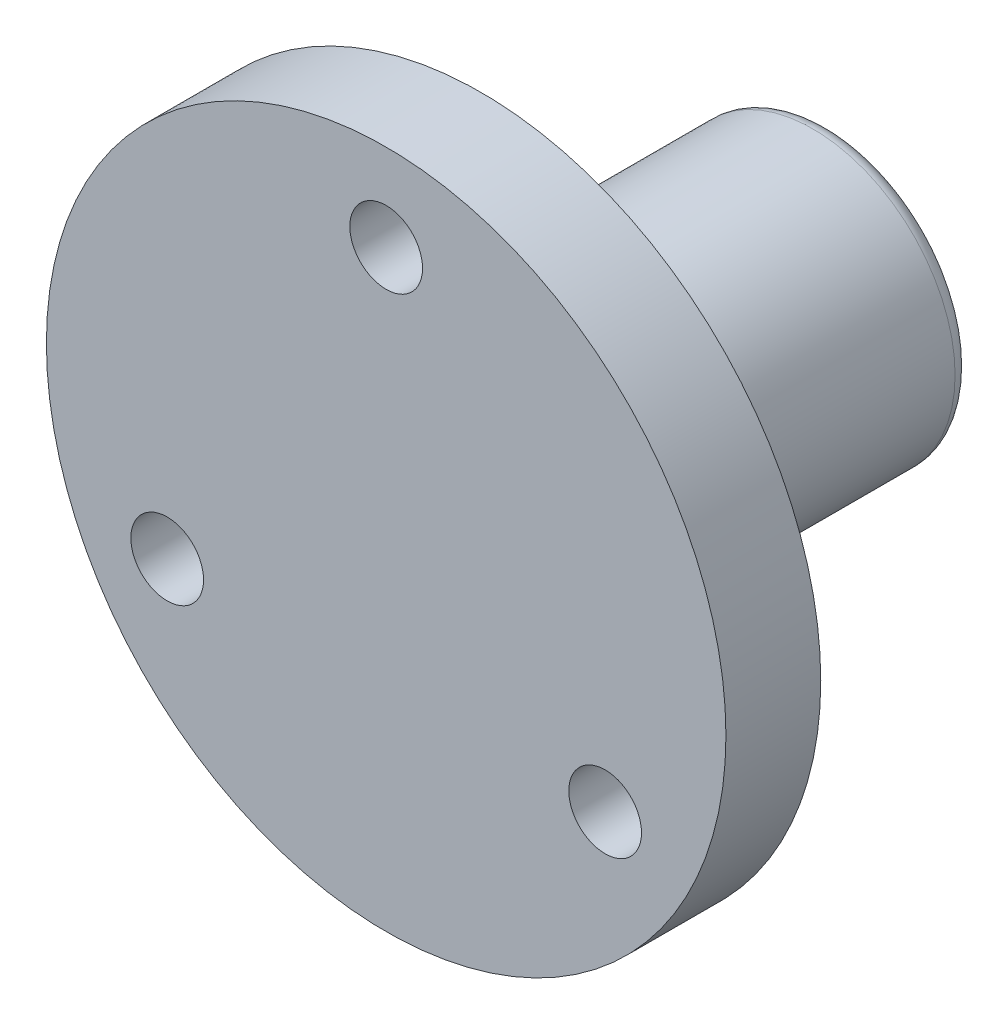
SolidWorks part; units mm, degrees
ref_plane "Front Plane" through (0, 0, 0) normal (0, 0, 1) x (1, 0, 0)
ref_plane "Top Plane" through (0, 0, 0) normal (0, 1, 0) x (1, 0, 0)
ref_plane "Right Plane" through (0, 0, 0) normal (1, 0, 0) x (0, 0, -1)
sketch "Sketch1" plane through (0, 0, 0) normal (0, 0, 1) x (1, 0, 0)
  line L1 (18.147, -4.5837) -> (21.703, -4.5837)
  line L2 (19.925, -4.5837) -> (19.925, -7) construction
  line L3 (18.147, -4.5837) -> (19.925, -7) construction
  arc A0 (18.147, -4.5837) -> (21.703, -4.5837) centre (19.925, -7) ccw
  circle A1 centre (19.925, -7) radius 4.5
  dimension "D1" = 1.5
  dimension "D2" = 36.347
  dimension "D3" = 3
extrude "Boss-Extrude1" add sketch "Sketch1" against normal blind 11
sketch "Sketch2" plane through (0, 0, 0) normal (0, 0, 1) x (1, 0, 0)
  line L0 (19.925, -7) -> (12.9968, -11) construction
  line L1 (19.925, -7) -> (19.925, 1) construction
  line L2 (19.925, -7) -> (26.8532, -11) construction
  circle A0 centre (19.925, -7) radius 10.75
  circle A3 centre (19.925, -7) radius 8 construction
  circle A4 centre (19.925, 1) radius 1.15
  circle A6 centre (12.9968, -11) radius 1.15
  circle A7 centre (26.8532, -11) radius 1.15
  dimension "D1" = 21.5
  dimension "D6" = 16
  dimension "D7" = 2.3
  dimension "D2" = 120
  dimension "D3" = 120
extrude "Boss-Extrude2" add sketch "Sketch2" along normal blind 3
sketch "Sketch3" plane through (0, 0, 0) normal (0, 0, -1) x (-1, 0, 0)
  line L0 (-19.925, -4.5837) -> (-19.925, -7) construction
  line L1 (-25.583, -8.8) -> (-28.1234, -8.8)
  line L2 (-28.1234, -8.8) -> (-29.3935, -11)
  line L3 (-29.3935, -11) -> (-28.1234, -13.2)
  line L4 (-28.1234, -13.2) -> (-25.583, -13.2)
  line L5 (-25.583, -13.2) -> (-24.3129, -11)
  line L6 (-24.3129, -11) -> (-25.583, -8.8)
  line L7 (-22.4653, 1) -> (-21.1952, -1.2)
  line L8 (-21.1952, -1.2) -> (-18.6548, -1.2)
  line L9 (-18.6548, -1.2) -> (-17.3847, 1)
  line L10 (-17.3847, 1) -> (-18.6548, 3.2)
  line L11 (-18.6548, 3.2) -> (-21.1952, 3.2)
  line L12 (-21.1952, 3.2) -> (-22.4653, 1)
  line L13 (-14.267, -8.8) -> (-15.5371, -11)
  line L14 (-15.5371, -11) -> (-14.267, -13.2)
  line L15 (-14.267, -13.2) -> (-11.7266, -13.2)
  line L16 (-11.7266, -13.2) -> (-10.4565, -11)
  line L17 (-10.4565, -11) -> (-11.7266, -8.8)
  line L18 (-11.7266, -8.8) -> (-14.267, -8.8)
  line L19 (-21.703, -4.5837) -> (-18.147, -4.5837) construction
  circle A0 centre (-26.8532, -11) radius 2.2 construction
  circle A1 centre (-19.925, 1) radius 2.2 construction
  circle A2 centre (-12.9968, -11) radius 2.2 construction
  dimension "D1" = 4.4
  dimension "D2" = 30
  dimension "D3" = 30
extrude "Cut-Extrude1" cut sketch "Sketch3" against normal blind 1
chamfer "Chamfer1" distance 1 angle 45 1 edges at (24.425, -7, 0)
fillet "Fillet1" radius 0.5 1 edges at (24.425, -7, -11)
